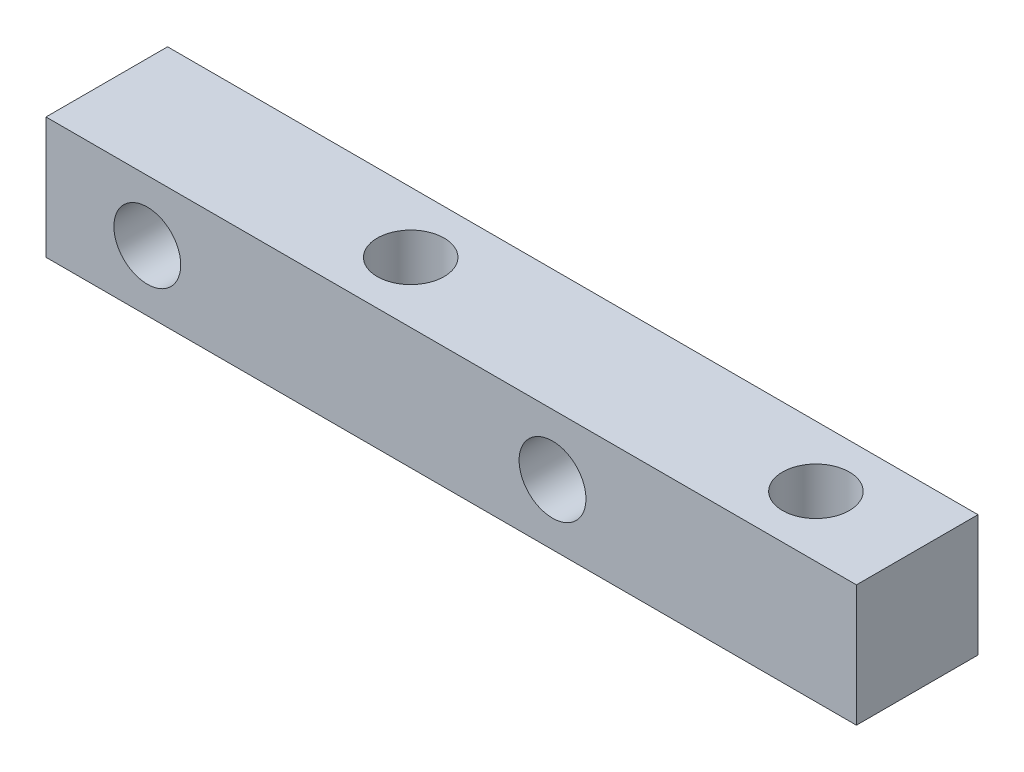
SolidWorks part; units mm, degrees
ref_plane "前视基准面" through (0, 0, 0) normal (0, 0, 1) x (1, 0, 0)
ref_plane "上视基准面" through (0, 0, 0) normal (0, 1, 0) x (1, 0, 0)
ref_plane "右视基准面" through (0, 0, 0) normal (1, 0, 0) x (0, 0, -1)
other "Configuration Table"
sketch "草图1" plane through (0, 0, 0) normal (1, 0, 0) x (0, 0, -1)
  line L1 (3, -3) -> (-3, -3)
  line L2 (3, -3) -> (3, 3)
  line L3 (3, 3) -> (-3, 3)
  line L4 (-3, -3) -> (-3, 3)
  line L5 (3, -3) -> (-3, 3) construction
  line L6 (3, 3) -> (-3, -3) construction
  point P0 (0, 0)
  dimension "D1" = 6
extrude "凸台-拉伸1" add sketch "草图1" along normal blind 40
sketch "草图2" plane through (0, 0, 3) normal (0, 0, 1) x (1, 0, 0)
  line L0 (0, 0) -> (24.1971, 0) construction
  line L1 (0, 3) -> (0, -3) construction
  circle A0 centre (5, 0) radius 1.65
  circle A1 centre (25, 0) radius 1.65
  dimension "D1" = 3.3
  dimension "D2" = 3.3
  dimension "D3" = 5
  dimension "D4" = 20
extrude "切除-拉伸1" cut sketch "草图2" against normal blind 6
sketch "草图3" plane through (0, 3, 0) normal (0, 1, 0) x (1, 0, 0)
  line L0 (0, 0) -> (42.3445, 0) construction
  line L1 (0, 3) -> (0, -3) construction
  circle A0 centre (15, 0) radius 1.65
  circle A1 centre (35, 0) radius 1.65
  dimension "D1" = 3.3
  dimension "D2" = 3.3
  dimension "D3" = 20
  dimension "D4" = 15
extrude "切除-拉伸2" cut sketch "草图3" against normal blind 6
